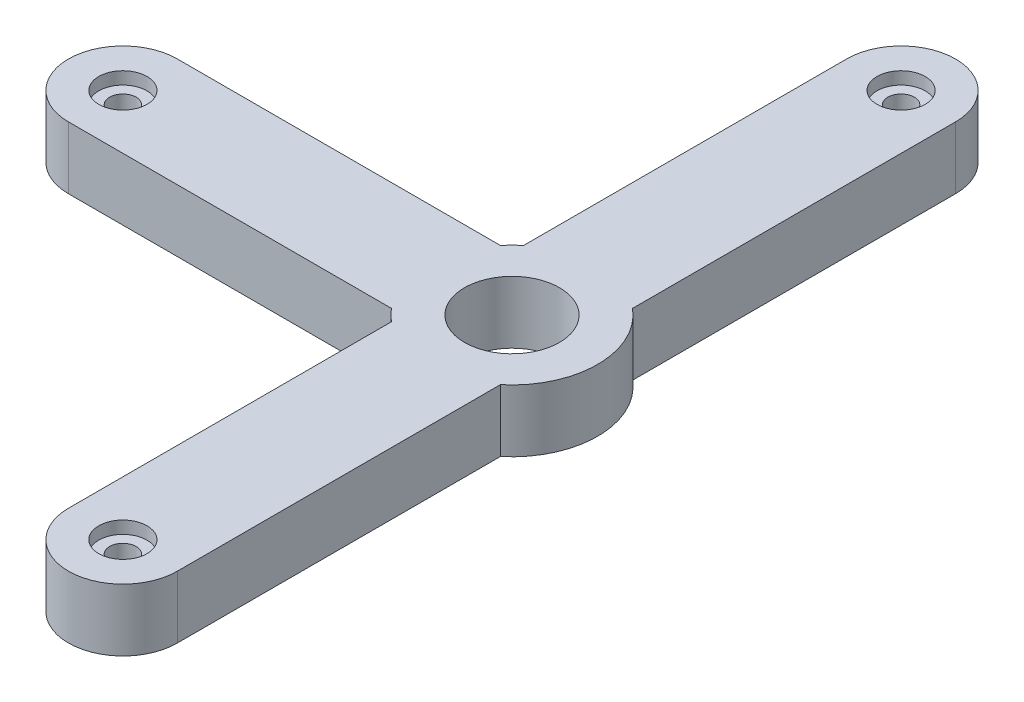
SolidWorks part; units mm, degrees
other "Rear Support Plate"
ref_plane "Front Plane" through (0, 0, 0) normal (0, 0, 1) x (1, 0, 0)
ref_plane "Top Plane" through (0, 0, 0) normal (0, 1, 0) x (1, 0, 0)
ref_plane "Right Plane" through (0, 0, 0) normal (1, 0, 0) x (0, 0, -1)
sketch3d "Base Outline Sketch datum points"
  point P0 (0, -157, 0)
  point P1 (10, -157, 0)
  point P2 (0, -157, -10)
ref_plane "Base Outline Sketch plane" through (0, -157, 0) normal (0, 1, 0) x (1, 0, 0)
sketch "Base Outline Sketch" plane through (0, -157, 0) normal (0, 1, 0) x (1, 0, 0)
  line L0 (-106.2917, -7) -> (-64.7769, -7)
  line L1 (-64.7769, 7) -> (-106.2917, 7)
  line L2 (-63.2917, -8.4853) -> (-63.2917, -50)
  line L3 (-63.2917, 50) -> (-63.2917, 8.4853)
  line L4 (-49.2917, -50) -> (-49.2917, -8.4853)
  line L5 (-49.2917, 8.4853) -> (-49.2917, 50)
  arc A0 (-106.2917, 7) -> (-106.2917, -7) centre (-106.2917, 0) ccw
  arc A1 (-64.7769, -7) -> (-63.2917, -8.4853) centre (-56.2917, 0) ccw
  arc A2 (-63.2917, 8.4853) -> (-64.7769, 7) centre (-56.2917, 0) ccw
  arc A3 (-63.2917, -50) -> (-49.2917, -50) centre (-56.2917, -50) ccw
  arc A4 (-49.2917, 50) -> (-63.2917, 50) centre (-56.2917, 50) ccw
  arc A5 (-49.2917, -8.4853) -> (-49.2917, 8.4853) centre (-56.2917, 0) ccw
  circle A6 centre (-106.2917, 0) radius 1.7
  circle A7 centre (-56.2917, 50) radius 1.7
  circle A8 centre (-56.2917, 9) radius 1.75
  circle A9 centre (-65.2917, 0) radius 1.75
  circle A10 centre (-56.2917, 0) radius 6.1
  circle A11 centre (-56.2917, -9) radius 1.75
  circle A12 centre (-56.2917, -50) radius 1.7
extrude "Base Outline" add sketch "Base Outline Sketch" along normal blind 4 separate body
sketch3d "Interface Profile 2 Sketch datum points"
  point P0 (0, -153, 0)
  point P1 (10, -153, 0)
  point P2 (0, -153, -10)
ref_plane "Interface Profile 2 Sketch plane" through (0, -153, 0) normal (0, 1, 0) x (1, 0, 0)
sketch "Interface Profile 2 Sketch" plane through (0, -153, 0) normal (0, 1, 0) x (1, 0, 0)
  line L0 (-106.2917, -7) -> (-64.7769, -7)
  line L1 (-64.7769, 7) -> (-106.2917, 7)
  line L2 (-63.2917, -8.4853) -> (-63.2917, -50)
  line L3 (-63.2917, 50) -> (-63.2917, 8.4853)
  line L4 (-49.2917, -50) -> (-49.2917, -8.4853)
  line L5 (-49.2917, 8.4853) -> (-49.2917, 50)
  arc A0 (-106.2917, 7) -> (-106.2917, -7) centre (-106.2917, 0) ccw
  arc A1 (-64.7769, -7) -> (-63.2917, -8.4853) centre (-56.2917, 0) ccw
  arc A2 (-63.2917, 8.4853) -> (-64.7769, 7) centre (-56.2917, 0) ccw
  arc A3 (-63.2917, -50) -> (-49.2917, -50) centre (-56.2917, -50) ccw
  arc A4 (-49.2917, 50) -> (-63.2917, 50) centre (-56.2917, 50) ccw
  arc A5 (-49.2917, -8.4853) -> (-49.2917, 8.4853) centre (-56.2917, 0) ccw
  circle A6 centre (-106.2917, 0) radius 1.7
  circle A7 centre (-56.2917, 50) radius 1.7
  circle A8 centre (-56.2917, 0) radius 6.1
  circle A9 centre (-56.2917, -50) radius 1.7
  circle A10 centre (-56.2917, 9) radius 1.1
  circle A11 centre (-65.2917, 0) radius 1.1
  circle A12 centre (-56.2917, -9) radius 1.1
extrude "Interface Profile 2" add sketch "Interface Profile 2 Sketch" along normal blind 2.4
sketch3d "Interface Profile 3 Sketch datum points"
  point P0 (0, -150.6, 0)
  point P1 (10, -150.6, 0)
  point P2 (0, -150.6, -10)
ref_plane "Interface Profile 3 Sketch plane" through (0, -150.6, 0) normal (0, 1, 0) x (1, 0, 0)
sketch "Interface Profile 3 Sketch" plane through (0, -150.6, 0) normal (0, 1, 0) x (1, 0, 0)
  line L0 (-106.2917, -7) -> (-64.7769, -7)
  line L1 (-64.7769, 7) -> (-106.2917, 7)
  line L2 (-63.2917, -8.4853) -> (-63.2917, -50)
  line L3 (-63.2917, 50) -> (-63.2917, 8.4853)
  line L4 (-49.2917, -50) -> (-49.2917, -8.4853)
  line L5 (-49.2917, 8.4853) -> (-49.2917, 50)
  arc A0 (-106.2917, 7) -> (-106.2917, -7) centre (-106.2917, 0) ccw
  arc A1 (-64.7769, -7) -> (-63.2917, -8.4853) centre (-56.2917, 0) ccw
  arc A2 (-63.2917, 8.4853) -> (-64.7769, 7) centre (-56.2917, 0) ccw
  arc A3 (-63.2917, -50) -> (-49.2917, -50) centre (-56.2917, -50) ccw
  arc A4 (-49.2917, 50) -> (-63.2917, 50) centre (-56.2917, 50) ccw
  arc A5 (-49.2917, -8.4853) -> (-49.2917, 8.4853) centre (-56.2917, 0) ccw
  circle A6 centre (-56.2917, 0) radius 6.1
  circle A7 centre (-106.2917, 0) radius 3.1
  circle A8 centre (-56.2917, 50) radius 3.1
  circle A9 centre (-56.2917, -50) radius 3.1
  circle A10 centre (-56.2917, 9) radius 1.1
  circle A11 centre (-65.2917, 0) radius 1.1
  circle A12 centre (-56.2917, -9) radius 1.1
extrude "Interface Profile 3" add sketch "Interface Profile 3 Sketch" along normal blind 0.6
sketch3d "Interface Profile 4 Sketch datum points"
  point P0 (0, -150, 0)
  point P1 (10, -150, 0)
  point P2 (0, -150, -10)
ref_plane "Interface Profile 4 Sketch plane" through (0, -150, 0) normal (0, 1, 0) x (1, 0, 0)
sketch "Interface Profile 4 Sketch" plane through (0, -150, 0) normal (0, 1, 0) x (1, 0, 0)
  line L0 (-106.2917, -7) -> (-64.7769, -7)
  line L1 (-64.7769, 7) -> (-106.2917, 7)
  line L2 (-63.2917, -8.4853) -> (-63.2917, -50)
  line L3 (-63.2917, 50) -> (-63.2917, 8.4853)
  line L4 (-49.2917, -50) -> (-49.2917, -8.4853)
  line L5 (-49.2917, 8.4853) -> (-49.2917, 50)
  arc A0 (-106.2917, 7) -> (-106.2917, -7) centre (-106.2917, 0) ccw
  arc A1 (-64.7769, -7) -> (-63.2917, -8.4853) centre (-56.2917, 0) ccw
  arc A2 (-63.2917, 8.4853) -> (-64.7769, 7) centre (-56.2917, 0) ccw
  arc A3 (-63.2917, -50) -> (-49.2917, -50) centre (-56.2917, -50) ccw
  arc A4 (-49.2917, 50) -> (-63.2917, 50) centre (-56.2917, 50) ccw
  arc A5 (-49.2917, -8.4853) -> (-49.2917, 8.4853) centre (-56.2917, 0) ccw
  circle A6 centre (-56.2917, 0) radius 6.1
  circle A7 centre (-106.2917, 0) radius 3.1
  circle A8 centre (-56.2917, 50) radius 3.1
  circle A9 centre (-56.2917, -50) radius 3.1
extrude "Interface Profile 4" add sketch "Interface Profile 4 Sketch" along normal blind 1
